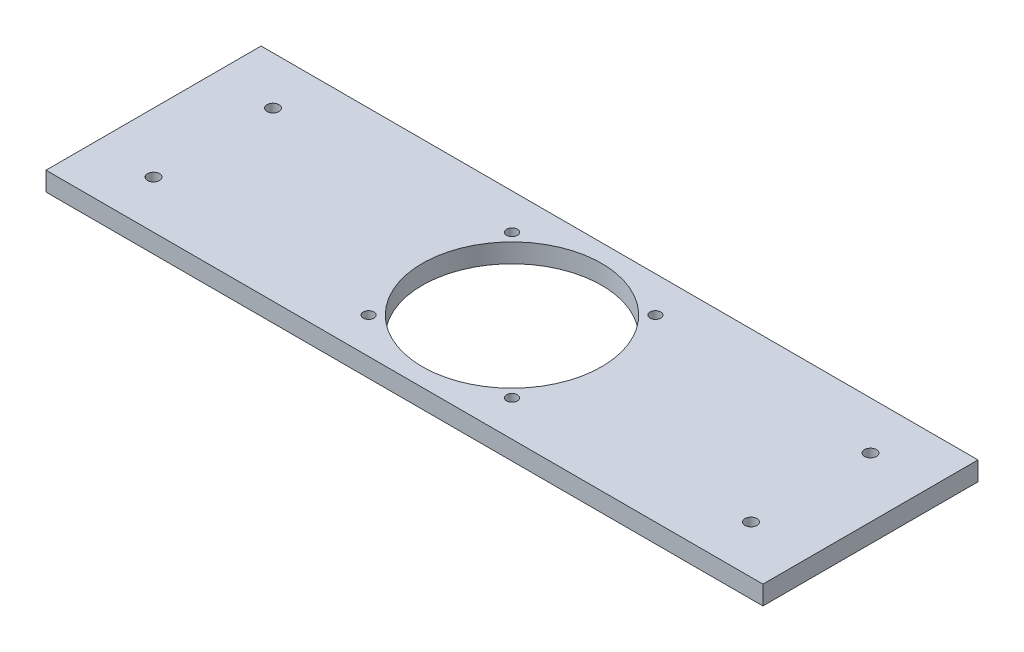
SolidWorks part; units mm, degrees
ref_plane "Front Plane" through (0, 0, 0) normal (0, 0, 1) x (1, 0, 0)
ref_plane "Top Plane" through (0, 0, 0) normal (0, 1, 0) x (1, 0, 0)
ref_plane "Right Plane" through (0, 0, 0) normal (1, 0, 0) x (0, 0, -1)
sketch "Sketch1" plane through (0, 0, 0) normal (0, 1, 0) x (1, 0, 0)
  line L1 (60, -18) -> (-60, -18)
  line L2 (60, -18) -> (60, 18)
  line L3 (60, 18) -> (-60, 18)
  line L4 (-60, -18) -> (-60, 18)
  line L5 (60, -18) -> (-60, 18) construction
  line L6 (60, 18) -> (-60, -18) construction
  point P0 (0, 0)
  dimension "D1" = 120
  dimension "D2" = 36
extrude "Boss-Extrude1" add sketch "Sketch1" along normal blind 3.175
sketch "Sketch2" plane through (0, 3.175, 0) normal (0, 1, 0) x (1, 0, 0)
  circle A0 centre (0, 0) radius 15
  dimension "D1" = 30
extrude "Cut-Extrude1" cut sketch "Sketch2" against normal blind 10
sketch "Sketch3" plane through (0, 3.175, 0) normal (0, 1, 0) x (1, 0, 0)
  line L1 (-12, 12) -> (12, 12) construction
  line L2 (-12, 12) -> (-12, -12) construction
  line L3 (-12, -12) -> (12, -12) construction
  line L4 (12, 12) -> (12, -12) construction
  line L5 (-12, 12) -> (12, -12) construction
  line L6 (-12, -12) -> (12, 12) construction
  circle A0 centre (12, 12) radius 0.9
  circle A1 centre (-12, 12) radius 0.9
  circle A2 centre (12, -12) radius 0.9
  circle A3 centre (-12, -12) radius 0.9
  point P0 (0, 0)
  dimension "D3" = 1.8
  dimension "D1" = 24
  dimension "D2" = 24
extrude "Cut-Extrude2" cut sketch "Sketch3" against normal blind 10
sketch "Sketch4" plane through (0, 3.175, 0) normal (0, 1, 0) x (1, 0, 0)
  line L1 (50, -10) -> (-50, -10) construction
  line L2 (50, -10) -> (50, 10) construction
  line L3 (50, 10) -> (-50, 10) construction
  line L4 (-50, -10) -> (-50, 10) construction
  line L5 (50, -10) -> (-50, 10) construction
  line L6 (50, 10) -> (-50, -10) construction
  circle A0 centre (-50, 10) radius 1
  circle A1 centre (50, 10) radius 1
  circle A2 centre (50, -10) radius 1
  circle A3 centre (-50, -10) radius 1
  point P0 (0, 0)
  dimension "D1" = 100
  dimension "D2" = 20
extrude "Cut-Extrude3" cut sketch "Sketch4" against normal blind 10
